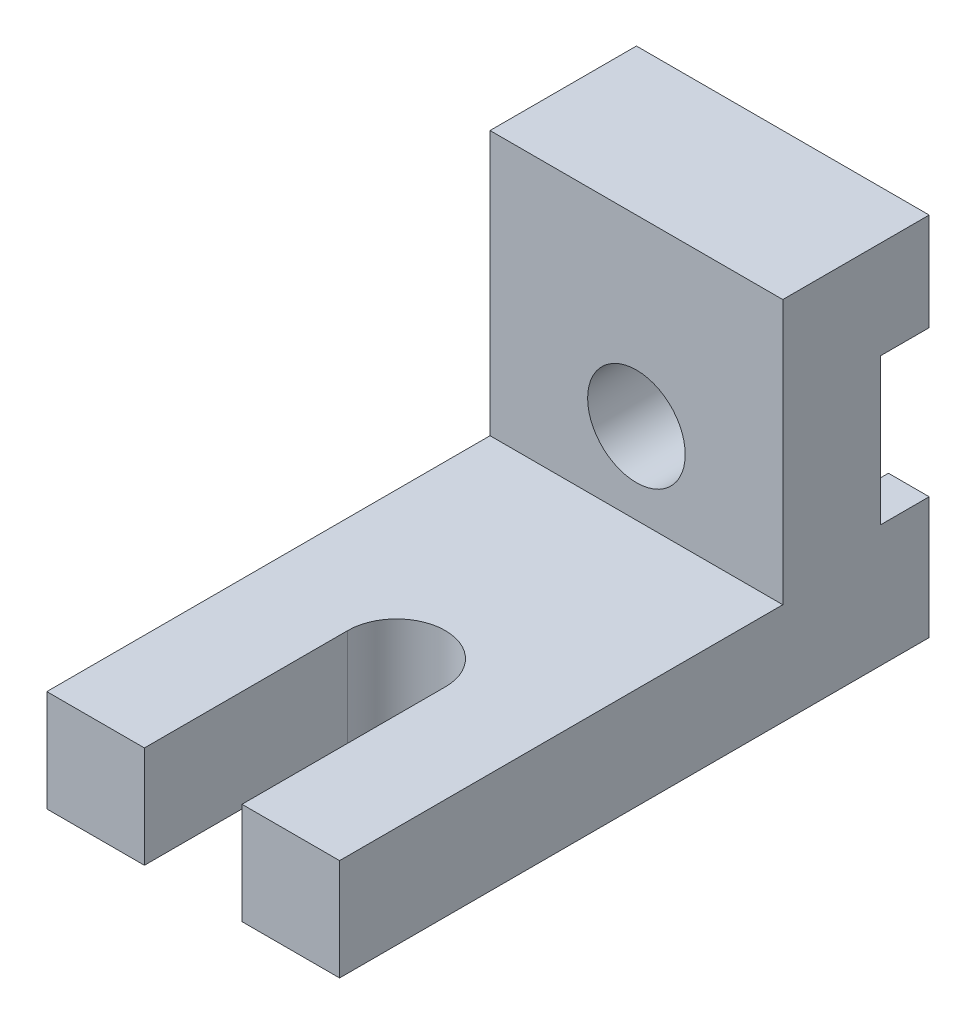
SolidWorks part; units mm, degrees
ref_plane "Front" through (0, 0, 0) normal (0, 0, 1) x (1, 0, 0)
ref_plane "Top" through (0, 0, 0) normal (0, 1, 0) x (1, 0, 0)
ref_plane "Right" through (0, 0, 0) normal (1, 0, 0) x (0, 0, -1)
sketch "Sketch1" plane through (0, 0, 0) normal (0, 0, 1) x (1, 0, 0)
  line L1 (914.4, -1143) -> (-914.4, -1143)
  line L2 (914.4, -1143) -> (914.4, 1143)
  line L3 (914.4, 1143) -> (-914.4, 1143)
  line L4 (-914.4, -1143) -> (-914.4, 1143)
  line L5 (914.4, -1143) -> (-914.4, 1143) construction
  line L6 (914.4, 1143) -> (-914.4, -1143) construction
  point P0 (0, 0)
  dimension "D1" = 2286
  dimension "D2" = 1828.8
extrude "Boss-Extrude1" add sketch "Sketch1" along normal blind 914.4
sketch "Sketch2" plane through (0, 0, 914.4) normal (0, 0, 1) x (1, 0, 0)
  line L0 (914.4, -1143) -> (914.4, 1143) construction
  line L1 (-914.4, -1143) -> (914.4, -1143)
  line L2 (-914.4, -1143) -> (-914.4, -508)
  line L3 (-914.4, -508) -> (914.4, -508)
  line L4 (914.4, -1143) -> (914.4, -508)
  dimension "D1" = 635
extrude "Boss-Extrude2" add sketch "Sketch2" along normal blind 2768.6
sketch "Sketch3" plane through (0, -508, 0) normal (0, 1, 0) x (1, 0, 0)
  line L0 (304.8, -3683) -> (304.8, -2413)
  line L1 (914.4, -3683) -> (-914.4, -3683) construction
  line L2 (-304.8, -3683) -> (-304.8, -2413)
  line L3 (914.4, -3683) -> (914.4, -914.4) construction
  line L4 (-914.4, -3683) -> (-914.4, -914.4) construction
  line L5 (304.8, -3683) -> (-304.8, -3683)
  arc A0 (304.8, -2413) -> (-304.8, -2413) centre (0, -2413) ccw
  dimension "D5" = 609.6
  dimension "D1" = 1270
  dimension "D2" = 609.6
  dimension "D3" = 609.6
  dimension "D4" = 609.6
extrude "Cut-Extrude1" cut sketch "Sketch3" against normal through all
sketch "Sketch4" plane through (0, -1143, 0) normal (0, -1, 0) x (1, 0, 0)
  line L1 (-914.4, 0) -> (355.6, 0)
  line L2 (-914.4, 0) -> (-914.4, 1828.8)
  line L3 (-914.4, 1828.8) -> (355.6, 1828.8)
  line L4 (355.6, 0) -> (355.6, 1828.8)
  dimension "D1" = 1270
  dimension "D2" = 1828.8
extrude "Cut-Extrude2" cut sketch "Sketch4" against normal blind 152.4
sketch "Sketch5" plane through (0, 0, 0) normal (0, 0, -1) x (-1, 0, 0)
  line L0 (-914.4, -1143) -> (-914.4, 1143) construction
  line L1 (-914.4, 533.4) -> (-544.1768, 533.4)
  line L2 (-914.4, 533.4) -> (-914.4, -381)
  line L3 (-914.4, -381) -> (-659.9114, -381)
  line L4 (914.4, 533.4) -> (914.4, -381)
  line L5 (914.4, 1143) -> (914.4, -990.6) construction
  line L6 (-914.4, 1143) -> (914.4, 1143) construction
  line L7 (-355.6, -1143) -> (-914.4, -1143) construction
  line L8 (544.1768, 533.4) -> (914.4, 533.4)
  line L9 (659.9114, -381) -> (914.4, -381)
  arc A0 (-659.9114, -381) -> (659.9114, -381) centre (0, 0) ccw
  arc A1 (544.1768, 533.4) -> (-544.1768, 533.4) centre (0, 0) ccw
  dimension "D3" = 1524
  dimension "D1" = 609.6
  dimension "D2" = 762
extrude "Cut-Extrude3" cut sketch "Sketch5" against normal blind 304.8
sketch "Sketch6" plane through (0, 0, 304.8) normal (0, 0, -1) x (-1, 0, 0)
  circle A0 centre (0, 0) radius 304.8
  dimension "D1" = 609.6
extrude "Cut-Extrude4" cut sketch "Sketch6" against normal through all
